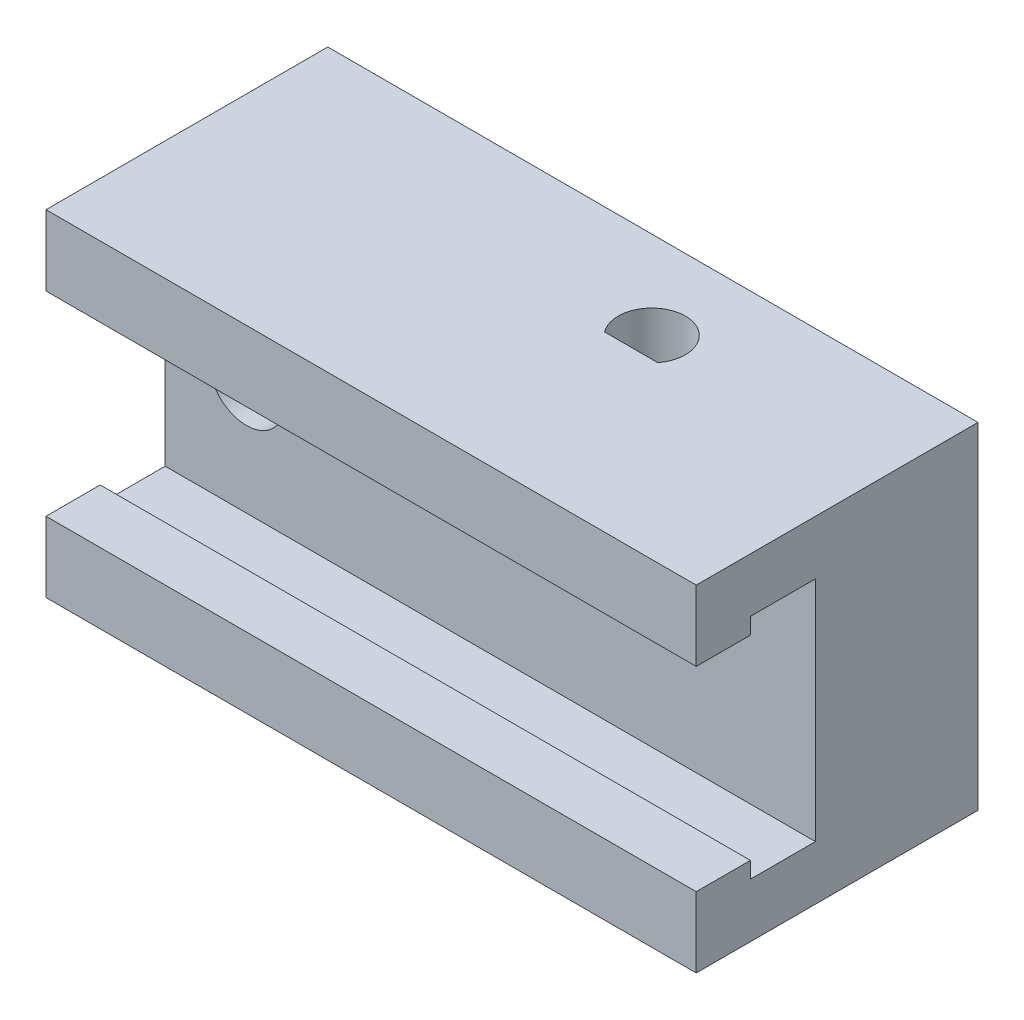
SolidWorks part; units mm, degrees
ref_plane "Front Plane" through (0, 0, 0) normal (0, 0, 1) x (1, 0, 0)
ref_plane "Top Plane" through (0, 0, 0) normal (0, 1, 0) x (1, 0, 0)
ref_plane "Right Plane" through (0, 0, 0) normal (1, 0, 0) x (0, 0, -1)
sketch "Sketch1" plane through (0, 0, 0) normal (0, 1, 0) x (1, 0, 0)
  line L0 (-1.2247, -0.95) -> (1.2247, -0.95)
  line L1 (-19, -3.45) -> (11, -3.45) construction
  line L2 (-19, 4.05) -> (11, 4.05)
  line L3 (-19, 4.05) -> (-19, -8.95)
  line L4 (-19, -8.95) -> (11, -8.95)
  line L5 (11, 4.05) -> (11, -8.95)
  line L6 (-19, -6.45) -> (11, -6.45) construction
  line L7 (-11, -14.7187) -> (11, -14.7187) construction
  arc A0 (1.2247, -0.95) -> (-1.2247, -0.95) centre (0, 0) ccw
  point P10 (0, 1.55)
  point P12 (4.0448, -14.7187)
  point P13 (0, -14.7187)
  point P16 (18.7091, -9.493)
  point P17 (11, -10.9513)
  point P19 (25.1501, -10.3842)
  point P20 (0, 0)
  dimension "D1" = 1.55
  dimension "D2" = 2.5
  dimension "D3" = 2.5
  dimension "D4" = 3
  dimension "D5" = 2.5
  dimension "D6" = 22
  dimension "D7" = 30
  dimension "D8" = 2.5
extrude "Boss-Extrude1" add sketch "Sketch1" along normal blind 15.5
sketch "Sketch2" plane through (-19, 0, 0) normal (-1, 0, 0) x (0, 0, 1)
  line L0 (8.95, 12.25) -> (6.45, 12.25)
  line L1 (6.45, 12.25) -> (6.45, 13)
  line L2 (6.45, 13) -> (3.45, 13)
  line L3 (3.45, 13) -> (3.45, 2.5)
  line L4 (3.45, 2.5) -> (6.45, 2.5)
  line L5 (6.45, 2.5) -> (6.45, 3.25)
  line L6 (6.45, 3.25) -> (8.95, 3.25)
  line L7 (8.95, 3.25) -> (8.95, 12.25)
  line L8 (8.95, 15.5) -> (8.95, 0) construction
  line L9 (3.45, 0) -> (3.45, 2.5) construction
  line L10 (6.45, 0) -> (6.45, 2.5) construction
  line L11 (-4.05, 0) -> (8.95, 0) construction
  line L12 (-4.05, 15.5) -> (8.95, 15.5) construction
  point P10 (8.95, 7.75)
  point P13 (0, 0)
  point P14 (0, 0)
  dimension "D1" = 2.5
  dimension "D2" = 2.5
  dimension "D3" = 9
extrude "Cut-Extrude1" cut sketch "Sketch2" against normal through all
sketch "Sketch3" plane through (0, 0, -4.05) normal (0, 0, -1) x (-1, 0, 0)
  line L0 (19, 15.5) -> (19, 0) construction
  circle A0 centre (15.25, 7.75) radius 1.75
  point P2 (0, 0)
  point P5 (19, 7.75)
  point P6 (13.5, 7.75)
  point P7 (0, 0)
  point P9 (11.9126, 7.75)
  dimension "D1" = 3.5
  dimension "D2" = 2.5
extrude "Cut-Extrude2" cut sketch "Sketch3" against normal through all
equation "\"D5@Sketch1\"=\"D3@Sketch1\""
equation "\"D8@Sketch1\"=\"D3@Sketch1\""
